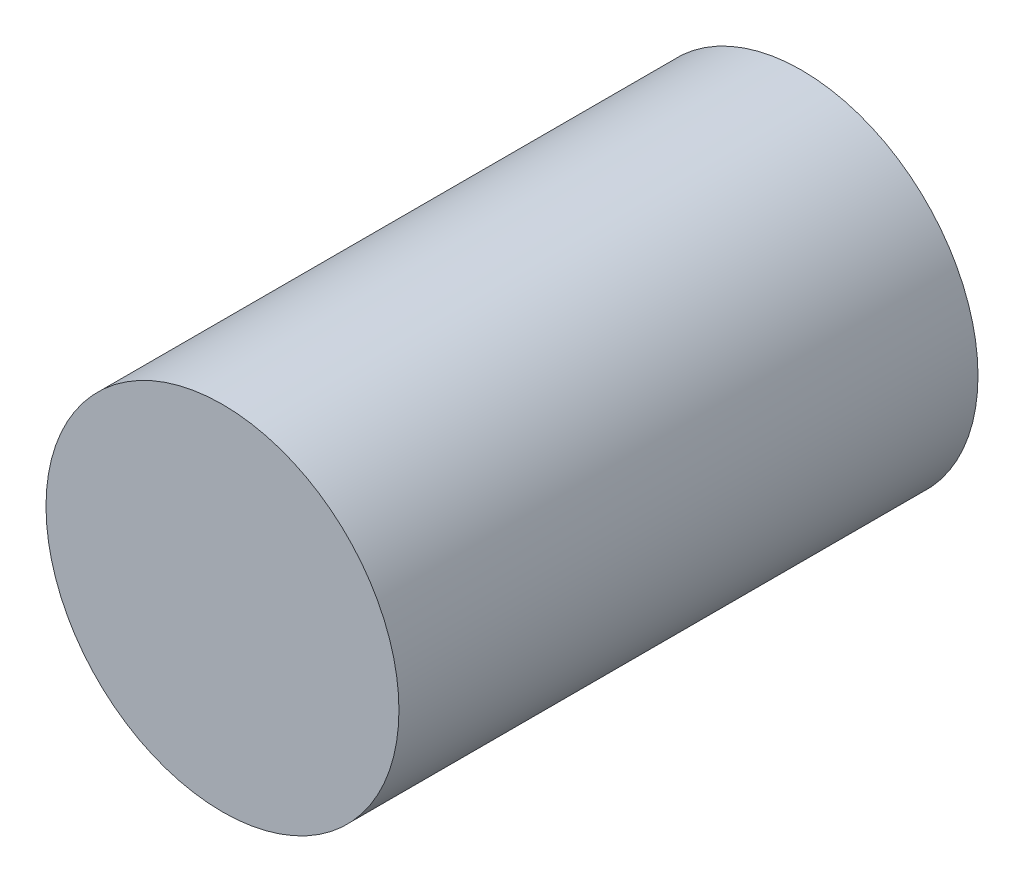
SolidWorks part; units mm, degrees
ref_plane "Alzado" through (0, 0, 0) normal (0, 0, 1) x (1, 0, 0)
ref_plane "Planta" through (0, 0, 0) normal (0, 1, 0) x (1, 0, 0)
ref_plane "Vista lateral" through (0, 0, 0) normal (1, 0, 0) x (0, 0, -1)
sketch "Croquis1" plane through (0, 0, 0) normal (0, 0, 1) x (1, 0, 0)
  circle A0 centre (0, 0) radius 6.4
extrude "Saliente-Extruir1" add sketch "Croquis1" along normal blind 21
